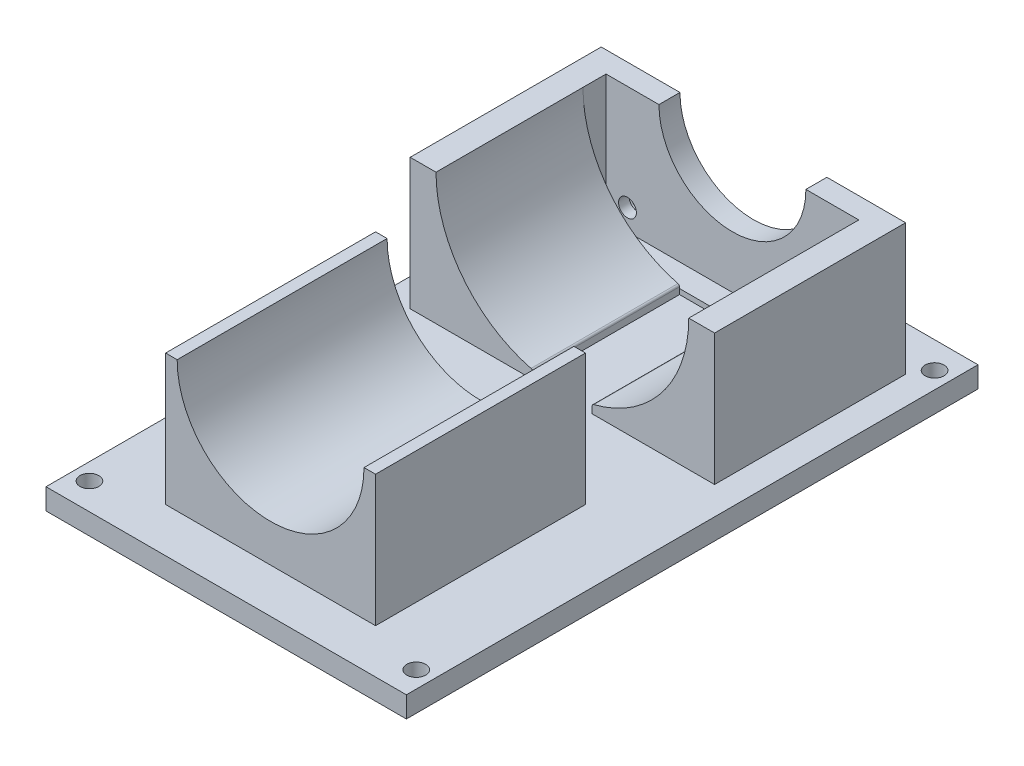
SolidWorks part; units mm, degrees
ref_plane "Front Plane" through (0, 0, 0) normal (0, 0, 1) x (1, 0, 0)
ref_plane "Top Plane" through (0, 0, 0) normal (0, 1, 0) x (1, 0, 0)
ref_plane "Right Plane" through (0, 0, 0) normal (1, 0, 0) x (0, 0, -1)
sketch "Sketch1" plane through (0, 0, 0) normal (0, 0, 1) x (1, 0, 0)
  line L0 (0, 72.5) -> (72.5, 0) construction
  line L1 (0, 0) -> (72.5, 0)
  line L2 (0, 0) -> (0, 72.5)
  line L3 (0, 72.5) -> (72.5, 72.5)
  line L4 (72.5, 0) -> (72.5, 72.5)
  line L6 (0, 0) -> (72.5, 72.5) construction
  circle A4 centre (36.25, 36.25) radius 17.5
  circle A5 centre (11.25, 61.25) radius 2.125
  circle A6 centre (61.25, 61.25) radius 2.125
  circle A7 centre (61.25, 11.25) radius 2.125
  circle A8 centre (11.25, 11.25) radius 2.125
  point P5 (11.25, 11.25)
  point P8 (61.25, 11.25)
  point P15 (36.25, 72.5)
  point P16 (0, 36.25)
  point P17 (61.25, 61.25)
  point P20 (11.25, 61.25)
  dimension "D1" = 50
  dimension "D8" = 35
  dimension "D4" = 4.25
  dimension "D2" = 50
  dimension "D3" = 72.5
extrude "Boss-Extrude1" add sketch "Sketch1" along normal blind 5
ref_plane "Plane1" through (0, 0, 65) normal (0, 0, 1) x (1, 0, 0)
sketch "Sketch18" plane through (0, 0, 0) normal (0, 0, 1) x (1, 0, 0)
  circle A0 centre (61.25, 61.25) radius 5
  circle A1 centre (11.25, 61.25) radius 5
  circle A2 centre (61.25, 11.25) radius 5
  circle A3 centre (11.25, 11.25) radius 5
  dimension "D1" = 10
sketch "Sketch5" plane through (0, 0, 65) normal (0, 0, 1) x (1, 0, 0)
  line L0 (0, 0) -> (72.5, 0)
  line L1 (11.25, 36.25) -> (14, 36.25)
  line L2 (11.25, 36.25) -> (11.25, 5)
  line L4 (0, 0) -> (0, 5)
  line L5 (0, 72.5) -> (0, 0) construction
  line L6 (0, 5) -> (11.25, 5)
  line L7 (36.25, 72.5) -> (36.25, 0) construction
  line L8 (72.5, 72.5) -> (0, 72.5) construction
  line L9 (72.5, 5) -> (61.25, 5)
  line L11 (72.5, 0) -> (72.5, 5)
  line L12 (61.25, 36.25) -> (58.5, 36.25)
  line L13 (61.25, 36.25) -> (61.25, 5)
  arc A2 (14, 36.25) -> (58.5, 36.25) centre (36.25, 36.25) ccw
  dimension "D4" = 22.25
  dimension "D2" = 5
  dimension "D3" = 25
extrude "Boss-Extrude2" add sketch "Sketch5" along normal blind 50 separate body
extrude "Cut-Extrude1" cut sketch "Sketch18" along direction (0, 0, -1) on the side of the normal blind 2.5
ref_plane "Plane4" through (0, 5, 0) normal (0, 1, 0) x (1, 0, 0)
sketch "Sketch7" plane through (0, 0, 5) normal (0, 0, 1) x (1, 0, 0)
  line L0 (0, 0) -> (72.5, 0)
  line L5 (72.5, 0) -> (72.5, 36.25)
  line L6 (72.5, 0) -> (72.5, 72.5) construction
  line L7 (72.5, 36.25) -> (66.35, 36.25)
  line L8 (66.35, 36.25) -> (66.35, 5)
  line L9 (72.5, 5) -> (61.25, 5) construction
  line L10 (66.35, 5) -> (6.15, 5)
  line L12 (6.15, 5) -> (6.15, 36.25)
  line L13 (6.15, 36.25) -> (0, 36.25)
  line L14 (0, 72.5) -> (0, 0) construction
  line L15 (0, 36.25) -> (0, 0)
  dimension "D1" = 60.2
extrude "Boss-Extrude3" add sketch "Sketch7" along normal blind 5.5
sketch "Sketch8" plane through (0, 0, 65) normal (0, 0, 1) x (1, 0, 0)
  line L1 (0, 0) -> (72.5, 0)
  line L2 (0, 0) -> (0, 5)
  line L3 (0, 5) -> (72.5, 5)
  line L4 (72.5, 0) -> (72.5, 5)
extrude "Boss-Extrude4" add sketch "Sketch8" against normal up to surface (54.5 mm away) up to face at (36.25, 19.375, 10.5)
ref_plane "Plane3" through (0, 0, 10.5) normal (0, 0, 1) x (1, 0, 0)
sketch "Sketch11" plane through (0, 0, 10.5) normal (0, 0, 1) x (1, 0, 0)
  line L0 (0, 5) -> (29.1474, 5)
  line L1 (66.35, 5) -> (6.15, 5) construction
  line L2 (72.5, 5) -> (43.3526, 5)
  line L3 (0, 72.5) -> (72.5, 0) construction
  line L4 (29.1474, 7) -> (29.1474, 5)
  line L5 (43.3526, 5) -> (43.3526, 7)
  line L12 (6.15, 36.25) -> (0, 36.25)
  line L13 (0, 36.25) -> (0, 5)
  line L14 (66.35, 36.25) -> (72.5, 36.25)
  line L15 (72.5, 36.25) -> (72.5, 5)
  arc A0 (6.15, 36.25) -> (29.1474, 7) centre (36.25, 36.25) ccw
  arc A1 (66.35, 36.25) -> (43.3526, 7) centre (36.25, 36.25) cw
  dimension "D1" = 2
extrude "Boss-Extrude5" add sketch "Sketch11" along normal blind 35
sketch "Sketch17" plane through (0, 5, 0) normal (0, 1, 0) x (1, 0, 0)
  line L0 (6.15, -5) -> (6.15, -10.5)
  line L1 (-37.8926, -10.5) -> (37.8926, -10.5) construction
  line L2 (6.15, -45.5) -> (6.15, -10.5) construction
  line L3 (6.15, -10.5) -> (66.4659, -10.5)
  line L4 (66.4659, -10.5) -> (66.35, -5)
  line L5 (66.35, -5) -> (6.15, -5)
extrude "Boss-Extrude7" add sketch "Sketch17" along normal blind 1.25
sketch "Sketch12" plane through (0, 0, 0) normal (0, 1, 0) x (1, 0, 0)
  line L0 (-6.6663, -125.5741) -> (79.1663, 10.5741) construction
  line L1 (-6.6663, 10.5741) -> (79.1663, -125.5741) construction
  line L2 (-6.6663, -125.5741) -> (79.1663, -125.5741)
  line L3 (-6.6663, -125.5741) -> (-6.6663, 10.5741)
  line L4 (-6.6663, 10.5741) -> (79.1663, 10.5741)
  line L5 (79.1663, -125.5741) -> (79.1663, 10.5741)
  line L6 (-3.3331, 10.5741) -> (-3.3331, -125.5741) construction
  line L8 (14.3178, 10.5741) -> (14.3178, 0) construction
  line L9 (72.5, 0) -> (0, 0) construction
  line L11 (75.8331, 10.5741) -> (75.8331, -125.5741) construction
  line L12 (72.5, -57.5) -> (79.1663, -57.5) construction
  line L14 (72.5, -45.5) -> (72.5, -5) construction
  line L15 (-6.6663, -3.6553) -> (0, -3.6553) construction
  line L16 (0, -5) -> (0, 0) construction
  circle A0 centre (-2.6665, 4.2296) radius 2.25
  circle A1 centre (75.1665, 4.2296) radius 2.25
  circle A2 centre (75.1665, -119.2296) radius 2.25
  circle A3 centre (-2.6665, -119.2296) radius 2.25
  point P21 (75.8331, -57.5)
  point P26 (-3.3331, -3.6553)
  dimension "D6" = 4.5
  dimension "D1" = 12.5
  dimension "D2" = 12.5
  dimension "D7" = 5
  dimension "D8" = 5
  dimension "D9" = 5
  dimension "D10" = 5
extrude "Boss-Extrude6" add sketch "Sketch12" along normal up to surface (5 mm away) up to face at (36.25, 5, 66.0833)
fillet "Fillet10" radius 0.5 2 edges at (43.3526, 7, 28) (29.1474, 7, 28)
ref_plane "Plane8" through (0, 0, 45.5) normal (0, 0, 1) x (1, 0, 0)
sketch "Sketch26" plane through (0, 0, 0) normal (0, 0, 1) x (1, 0, 0)
  line L1 (0, 72.5) -> (72.5, 72.5)
  line L2 (0, 72.5) -> (0, 36.25)
  line L3 (0, 36.25) -> (72.5, 36.25)
  line L4 (72.5, 72.5) -> (72.5, 36.25)
  dimension "D1" = 36.25
extrude "Cut-Extrude3" cut sketch "Sketch26" along normal through all
